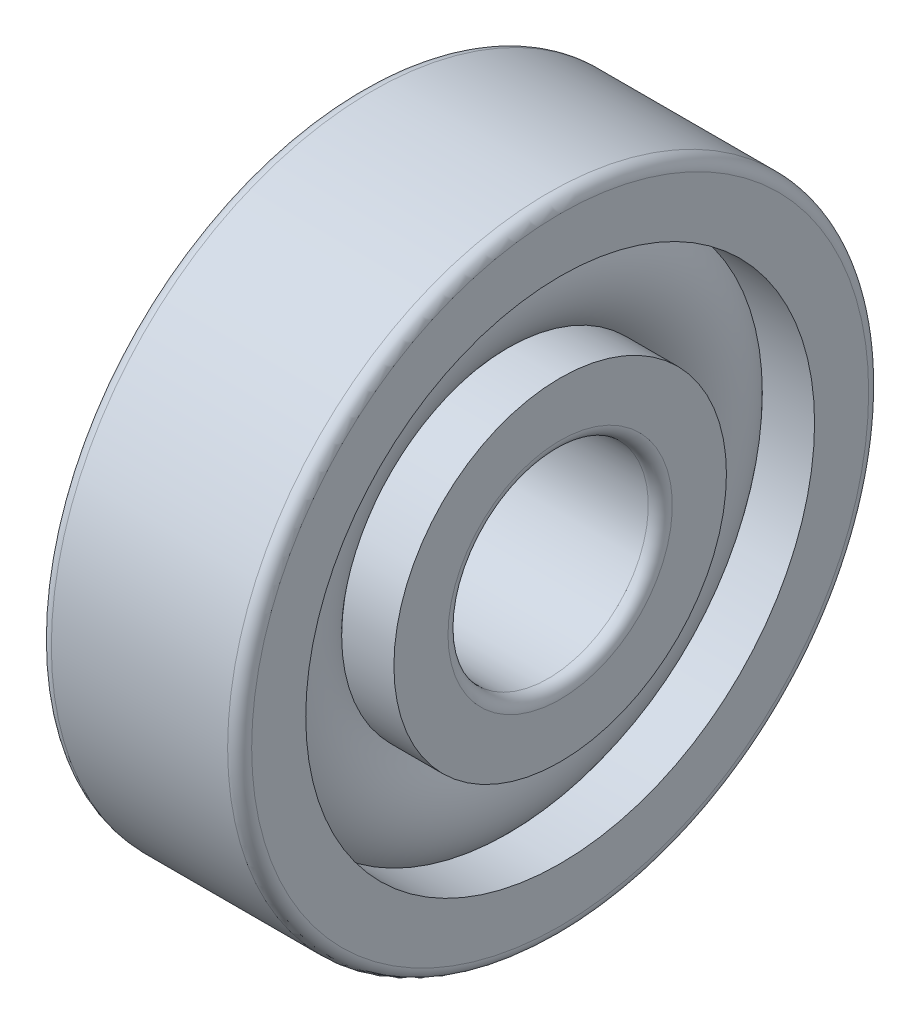
SolidWorks part; units mm, degrees
ref_plane "Front Plane" through (0, 0, 0) normal (0, 0, 1) x (1, 0, 0)
ref_plane "Top Plane" through (0, 0, 0) normal (0, 1, 0) x (1, 0, 0)
ref_plane "Right Plane" through (0, 0, 0) normal (1, 0, 0) x (0, 0, -1)
sketch "ralla" plane through (0, 0, 0) normal (0, 0, 1) x (1, 0, 0)
  line L0 (-1.1961, 4.15) -> (-2.5, 4.15)
  line L1 (-2.5, 4.15) -> (-2.5, 2.8)
  line L2 (-2.2, 2.5) -> (2.2, 2.5)
  line L3 (2.5, 2.8) -> (2.5, 4.15)
  line L4 (2.5, 4.15) -> (1.1961, 4.15)
  line L5 (-3.6338, 0) -> (3.6338, 0) construction
  line L6 (0, 0) -> (0, 12.075) construction
  line L7 (-1.1961, 6.35) -> (-2.5, 6.35)
  line L8 (-2.5, 6.35) -> (-2.5, 7.7)
  line L9 (-2.2, 8) -> (2.2, 8)
  line L10 (2.5, 7.7) -> (2.5, 6.35)
  line L11 (2.5, 6.35) -> (1.1961, 6.35)
  line L13 (0, 0) -> (0, 12.075) construction
  arc A0 (-2.5, 2.8) -> (-2.2, 2.5) centre (-2.2, 2.8) ccw
  arc A1 (2.2, 2.5) -> (2.5, 2.8) centre (2.2, 2.8) ccw
  arc A2 (1.1961, 4.15) -> (-1.1961, 4.15) centre (0, 5.25) cw
  arc A3 (-2.5, 7.7) -> (-2.2, 8) centre (-2.2, 7.7) cw
  arc A4 (2.2, 8) -> (2.5, 7.7) centre (2.2, 7.7) cw
  arc A5 (1.1961, 6.35) -> (-1.1961, 6.35) centre (0, 5.25) ccw
  point P27 (0, 0)
  dimension "D5" = 2.5
  dimension "D7" = 1.625
  dimension "D10" = 0.3
  dimension "D11" = 0.3
  dimension "D2" = 2.2
  dimension "D3" = 1.65
  dimension "D4" = 1.65
  dimension "D6" = 2.5
  dimension "D8" = 1.1961
  dimension "D9" = 1.1961
  dimension "D12" = 8
  dimension "D13" = 2.5
sketch "Sketch2" plane through (0, 0, 0) normal (0, 0, 1) x (1, 0, 0)
  circle A0 centre (0, 5.25) radius 1.625
revolve "Revolve1" add sketch "ralla" angle 360 about L5
surface "Surface-Revolve1" sketch "Sketch2" parameters "D1"=360
